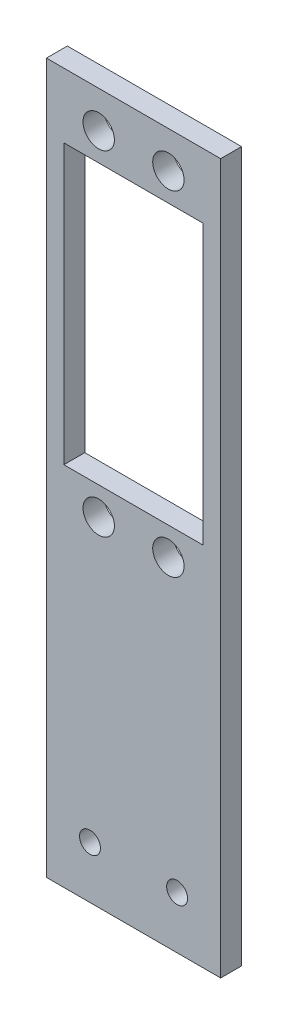
SolidWorks part; units mm, degrees
ref_plane "Front Plane" through (0, 0, 0) normal (0, 0, 1) x (1, 0, 0)
ref_plane "Top Plane" through (0, 0, 0) normal (0, 1, 0) x (1, 0, 0)
ref_plane "Right Plane" through (0, 0, 0) normal (1, 0, 0) x (0, 0, -1)
sketch "Sketch1" plane through (0, 0, 0) normal (0, 0, 1) x (1, 0, 0)
  line L0 (0, 15) -> (0, 101.812)
  line L5 (0, 0) -> (25, 0)
  line L6 (0, 0) -> (0, 15)
  line L7 (0, 15) -> (25, 15)
  line L8 (25, 0) -> (25, 15)
  line L9 (12.5, 15) -> (12.5, 0) construction
  line L10 (0, 7.5) -> (25, 7.5) construction
  line L11 (0, 101.812) -> (25, 101.812)
  line L12 (25, 101.812) -> (25, 15)
  line L13 (7.5, 96.53) -> (17.5, 96.53) construction
  line L14 (2.5, 92.53) -> (22.5, 92.53)
  line L15 (2.5, 92.53) -> (2.5, 52.53)
  line L16 (2.5, 52.53) -> (22.5, 52.53)
  line L17 (22.5, 92.53) -> (22.5, 52.53)
  line L18 (2.5, 92.53) -> (22.5, 52.53) construction
  line L19 (2.5, 52.53) -> (22.5, 92.53) construction
  line L20 (12.5, 96.53) -> (12.5, 48.53)
  line L21 (7.5, 48.53) -> (17.5, 48.53)
  line L22 (12.5, 7.5) -> (0, 7.5) construction
  line L23 (12.5, 7.5) -> (25, 7.5) construction
  circle A0 centre (12.5, 82.5) radius 1.3502
  circle A1 centre (7.5, 96.53) radius 2.25
  circle A2 centre (17.5, 96.53) radius 2.25
  circle A3 centre (7.5, 48.53) radius 2.25
  circle A4 centre (17.5, 48.53) radius 2.25
  circle A5 centre (6.25, 7.5) radius 1.5
  circle A6 centre (18.75, 7.5) radius 1.5
  point P19 (12.5, 48.53)
  point P21 (12.5, 96.53)
  point P153 (12.5, 7.5)
  point P237 (12.5, 72.53)
  dimension "D9" = 4.5
  dimension "D11" = 3
  dimension "D1" = 25
  dimension "D2" = 15
  dimension "D3" = 48
  dimension "D4" = 20
  dimension "D5" = 40
  dimension "D6" = 67.5
  dimension "D7" = 10
  dimension "D8" = 14.03
  dimension "D10" = 10
extrude "Boss-Extrude1" add sketch "Sketch1" along normal blind 3
